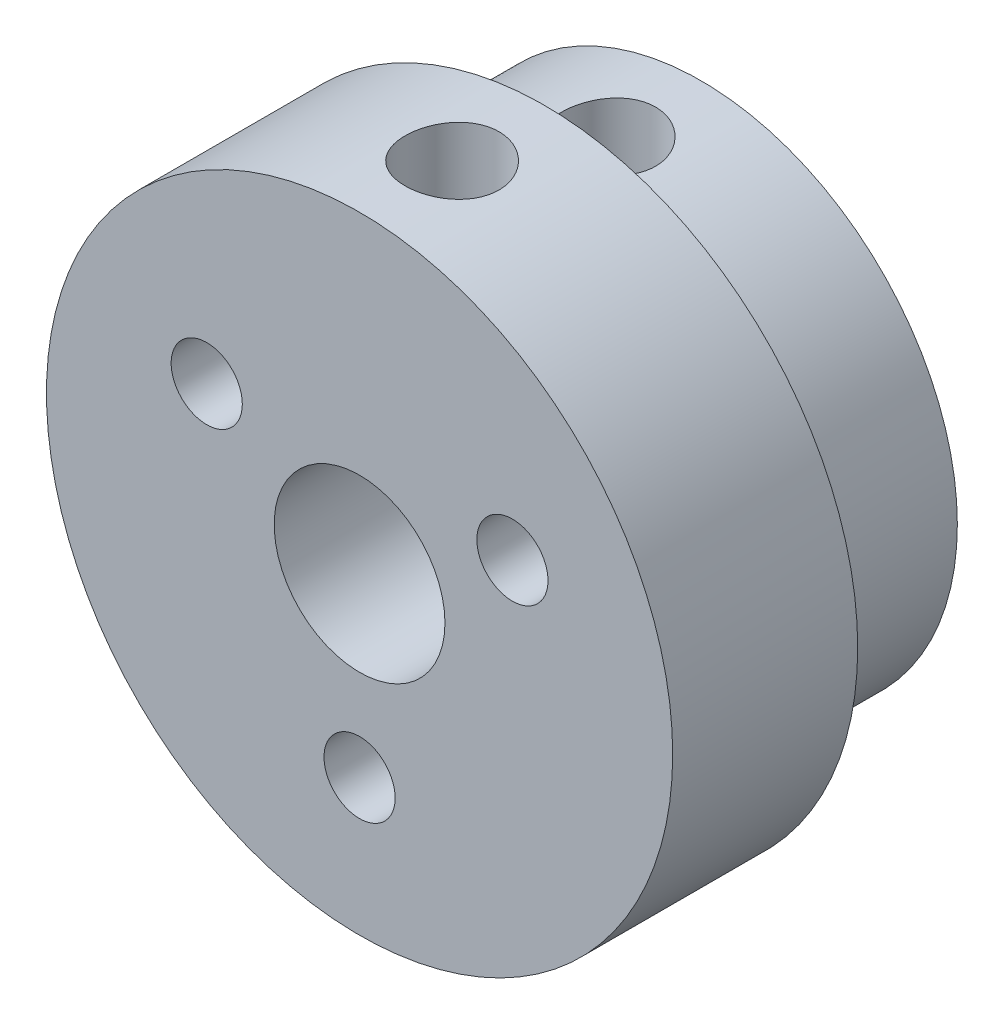
SolidWorks part; units mm, degrees
ref_plane "Front Plane" through (0, 0, 0) normal (0, 0, 1) x (1, 0, 0)
ref_plane "Top Plane" through (0, 0, 0) normal (0, 1, 0) x (1, 0, 0)
ref_plane "Right Plane" through (0, 0, 0) normal (1, 0, 0) x (0, 0, -1)
sketch "Sketch2" plane through (0, 0, 0) normal (1, 0, 0) x (0, 0, -1)
  line L0 (0, 3) -> (0, 11)
  line L1 (0, 11) -> (6.5, 11)
  line L2 (6.5, 11) -> (6.5, 9)
  line L3 (6.5, 9) -> (12, 9)
  line L4 (12, 9) -> (12, 3)
  line L5 (12, 3) -> (0, 3)
  line L6 (0, 0) -> (12.875, 0) construction
  dimension "D1" = 3
  dimension "D2" = 22
  dimension "D3" = 18
  dimension "D4" = 6.5
  dimension "D5" = 5.5
revolve "Revolve1" add sketch "Sketch2" angle 360 about L6
sketch "Sketch3" plane through (0, 0, 0) normal (0, 0, 1) x (1, 0, 0)
  line L7 (5.3694, 3.1) -> (-5.3694, 3.1) construction
  line L8 (-5.3694, 3.1) -> (0, -6.2) construction
  line L9 (0, -6.2) -> (5.3694, 3.1) construction
  circle A0 centre (0, 0) radius 6.2 construction
  circle A1 centre (0, 0) radius 6.2 construction
  dimension "D1" = 12.4
hole_wizard "M3x0.5 Tapped Hole1" positions "Sketch4" profile "Sketch5" tap size "M3x0.5" standard "ANSI Metric" end condition through all
sketch "Sketch4" plane through (0, 0, 0) normal (0, 0, 1) x (1, 0, 0)
  point P18 (35.9105, 13.4709)
  point P19 (5.3694, 3.1)
  point P22 (-5.3694, 3.1)
  point P25 (0, -6.2)
sketch "Sketch5" plane through (35.9105, 13.4709, 0) normal (1, 0, 0) x (0, -1, 0)
  line L0 (0, 0) -> (0, 12)
  line L1 (0, 12) -> (1.25, 12)
  line L2 (1.25, 12) -> (1.25, 0)
  line L5 (1.25, 0) -> (0, 0)
  line L11 (0, -6.35) -> (0, 107.95) construction
  dimension "Thru Tap Drill Dia." = 2.5
  dimension "Thru Tap Drill Depth" = 12
cosmetic thread "Hole Thread3" parameters "D2"=3
cosmetic thread "Hole Thread4" parameters "D2"=3
cosmetic thread "Hole Thread5" parameters "D2"=3
sketch "Sketch6" plane through (0, 0, 0) normal (1, 0, 0) x (0, 0, -1)
  line L0 (0, 11) -> (6.5, 11)
  line L1 (5, -12.7) -> (0, -12.7)
  line L3 (0, 11) -> (6.5, 11) construction
  line L4 (6.5, 9) -> (12, 9)
  line L5 (9.2, -6) -> (5, -6)
  line L7 (6.5, 9) -> (12, 9) construction
  point P8 (3.25, 11)
  point P9 (8.75, 9)
  dimension "D1" = 3.25
hole_wizard "M4x0.7 Tapped Hole1" positions "3DSketch1" profile "Sketch8" tap size "M4x0.7" standard "ANSI Metric"
sketch3d "3DSketch1"
  line L0 (0, 11, 0) -> (0, 11, -6.5) construction
  point P0 (0, 11, -3.25)
  point P3 (0, 9, -8.75)
  point P6 (0, 11, -3.25)
  point P12 (0, 11, -3.25)
  point P14 (0, 11, -3.25)
  point P16 (0, 9, -8.75)
  point P18 (0, 11, -3.25)
  point P21 (0, 11, -3.25)
  point P23 (0, 11, -3.25)
  point P25 (0, 9, -8.75)
sketch "Sketch8" plane through (0, 9, -8.75) normal (1, 0, 0) x (0, 0, 1)
  line L0 (0, 0) -> (0, 11.9904)
  line L1 (0, 11.9904) -> (1.65, 10.999)
  line L2 (1.65, 10.999) -> (1.65, 0)
  line L5 (1.65, 0) -> (0, 0)
  line L10 (0, 11.9904) -> (-1.65, 10.999) construction
  line L11 (0, -6.35) -> (0, 107.95) construction
  dimension "Tap Drill Dia." = 3.3
  dimension "Tap Drill Depth" = 10.999
  dimension "Drill Angle" = 118
cosmetic thread "Hole Thread1" parameters "D1"=6.4945, "D2"=4
cosmetic thread "Hole Thread2" parameters "D1"=8, "D2"=4
